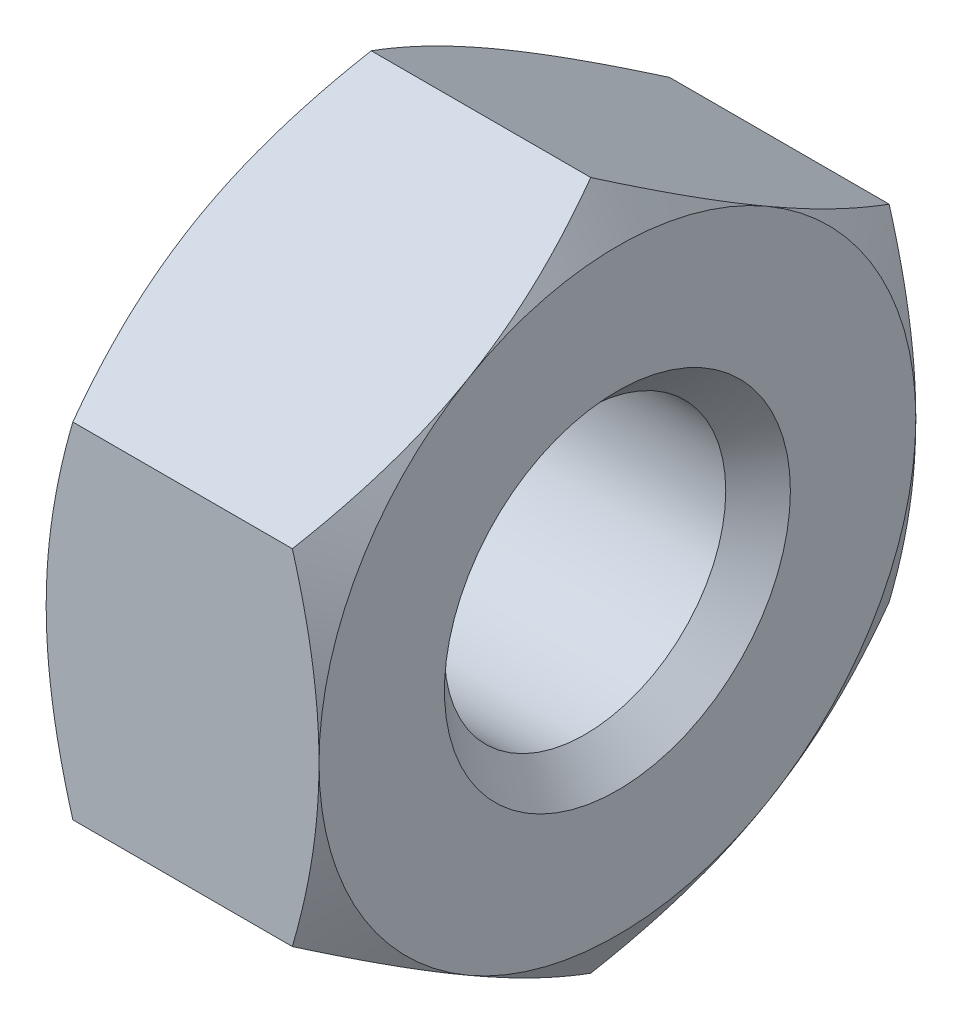
SolidWorks part; units mm, degrees
material "Plain Carbon Steel"
ref_plane "Front Plane" through (0, 0, 0) normal (0, 0, 1) x (1, 0, 0)
ref_plane "Top Plane" through (0, 0, 0) normal (0, 1, 0) x (1, 0, 0)
ref_plane "Right Plane" through (0, 0, 0) normal (1, 0, 0) x (0, 0, -1)
sketch "Sketch1" plane through (0, 0, 0) normal (1, 0, 0) x (0, 0, -1)
  line L0 (3.5, 2.0207) -> (3.5, -2.0207)
  line L1 (-3.5, 2.0207) -> (-3.5, -2.0207)
  line L2 (3.5, 2.0207) -> (0, 4.0415)
  line L3 (0, 4.0415) -> (-3.5, 2.0207)
  line L4 (-3.5, -2.0207) -> (0, -4.0415)
  line L5 (0, -4.0415) -> (3.5, -2.0207)
  circle A0 centre (0, 0) radius 1.65
  dimension "D3" = 3.3
  dimension "D1" = 7
  dimension "D2" = 120
  dimension "D4" = 3.5
extrude "Boss-Extrude1" add sketch "Sketch1" along normal mid plane 3.2
sketch "Sketch2" plane through (-1.6, 0, 0) normal (-1, 0, 0) x (0, 0, 1)
  line L0 (-3.5, -2.0207) -> (-3.5, 2.0207) construction
  line L1 (-3.5, 2.0207) -> (0, 4.0415) construction
  line L2 (0, 4.0415) -> (3.5, 2.0207) construction
  line L3 (3.5, 2.0207) -> (3.5, -2.0207) construction
  line L4 (3.5, -2.0207) -> (0, -4.0415) construction
  line L5 (0, -4.0415) -> (-3.5, -2.0207) construction
  line L6 (-3.5, -2.0207) -> (-3.5, 2.0207) construction
  line L7 (-3.5, 2.0207) -> (0, 4.0415) construction
  line L8 (0, 4.0415) -> (3.5, 2.0207) construction
  line L9 (3.5, 2.0207) -> (3.5, -2.0207) construction
  line L10 (3.5, -2.0207) -> (0, -4.0415) construction
  line L11 (0, -4.0415) -> (-3.5, -2.0207) construction
  circle A0 centre (0, 0) radius 3.5 construction
sketch "Sketch4" plane through (0, 0, 0) normal (0, 0, 1) x (1, 0, 0)
  line L0 (-1.6, 3.5) -> (-1.6, -3.5) construction
  line L1 (-1.6, 3.5) -> (-1.6, -3.5) construction
  line L2 (-1.6, 3.5) -> (-1.6, 5.2275)
  line L3 (-1.6, 5.2275) -> (-0.6026, 5.2275)
  line L4 (-0.6026, 5.2275) -> (-1.6, 3.5)
  line L5 (-2.7191, 0) -> (4.5055, 0) construction
  dimension "D1" = 30
revolve "Cut-Revolve1" cut sketch "Sketch4" angle 360 about L5
mirror "Mirror1" about plane through (0, 0, 0) normal (1, 0, 0) of "Cut-Revolve1"
ref_plane "Plane1" through (2.3, 0, 0) normal (1, 0, 0) x (0, 0, -1)
chamfer "Chamfer1" distance 0.379 angle 45 2 edges at (-1.6, 0, -1.65) (1.6, 0, -1.65)
